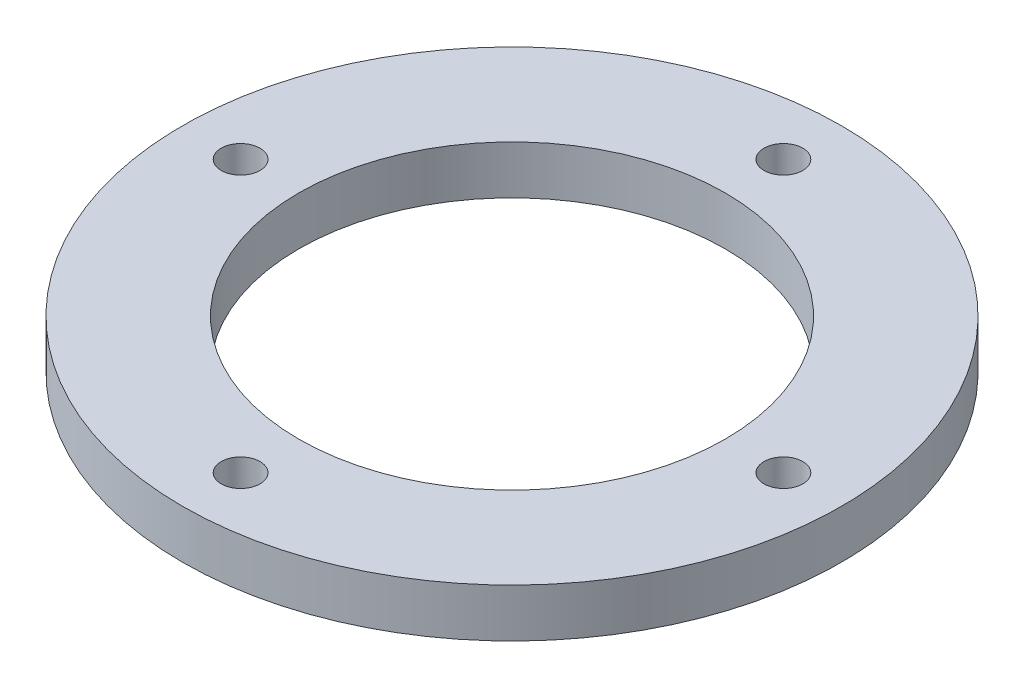
SolidWorks part; units mm, degrees
material "1060 合金"
ref_plane "前视基准面" through (0, 0, 0) normal (0, 0, 1) x (1, 0, 0)
ref_plane "上视基准面" through (0, 0, 0) normal (0, 1, 0) x (1, 0, 0)
ref_plane "右视基准面" through (0, 0, 0) normal (1, 0, 0) x (0, 0, -1)
sketch "草图1" plane through (0, 0, 0) normal (0, 1, 0) x (1, 0, 0)
  circle A0 centre (0, 0) radius 34
extrude "凸台-拉伸1" add sketch "草图1" along normal blind 5
sketch "草图2" plane through (0, 5, 0) normal (0, 1, 0) x (1, 0, 0)
  circle A0 centre (0, 0) radius 22
extrude "切除-拉伸1" cut sketch "草图2" against normal blind 5
sketch "草图3" plane through (0, 5, 0) normal (0, 1, 0) x (1, 0, 0)
  circle A0 centre (0, 28) radius 2
extrude "切除-拉伸2" cut sketch "草图3" against normal blind 5
pattern_circular "阵列(圆周)1" count 4 over 360 about axis through (0, 0, 0) along (0, 1, 0) of "切除-拉伸2"
fillet "圆角1" [suppressed] radius 0.3
